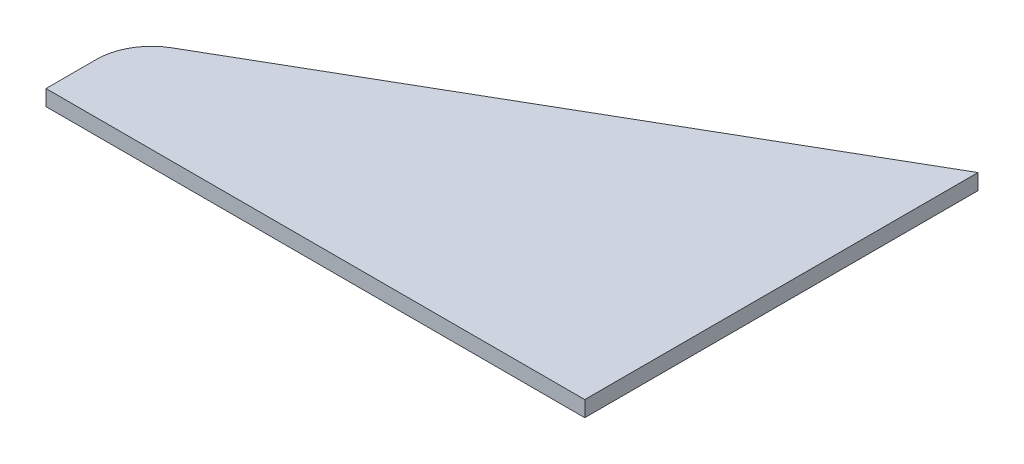
SolidWorks part; units mm, degrees
material "Acrylic (Medium-high impact)"
ref_plane "Front Plane" through (0, 0, 0) normal (0, 0, 1) x (1, 0, 0)
ref_plane "Top Plane" through (0, 0, 0) normal (0, 1, 0) x (1, 0, 0)
ref_plane "Right Plane" through (0, 0, 0) normal (1, 0, 0) x (0, 0, -1)
sketch "Sketch1" plane through (0, 0, 0) normal (0, 1, 0) x (1, 0, 0)
  line L1 (-233.3625, 0) -> (233.3625, 0) construction
  line L2 (-233.3625, 0) -> (-233.3625, 158.75)
  line L4 (233.3625, 0) -> (233.3625, 158.75)
  line L6 (0, 0) -> (0, 39.5993) construction
  line L7 (-26.9875, 39.5993) -> (-233.3625, 158.75)
  line L8 (233.3625, 158.75) -> (26.9875, 39.5993)
  line L9 (-15.875, 20.3519) -> (-15.875, 0)
  line L10 (15.875, 20.3519) -> (15.875, 0)
  line L11 (-233.3625, 0) -> (-15.875, 0)
  line L12 (15.875, 0) -> (233.3625, 0)
  arc A1 (-26.9875, 39.5993) -> (-15.875, 20.3519) centre (-38.1, 20.3519) cw
  arc A2 (26.9875, 39.5993) -> (15.875, 20.3519) centre (38.1, 20.3519) ccw
  point P4 (0, 0)
  dimension "D5" = 22.225
  dimension "D1" = 466.725
  dimension "D2" = 158.75
  dimension "D3" = 60
  dimension "D4" = 31.75
extrude "Boss-Extrude1" add sketch "Sketch1" along normal blind 6.35 contours A1 L7 L2 L11 L9 | L8 A2 L10 L12 L4
delete or keep bodies "Body-Delete/Keep 1" type delete bodies bodies 106
